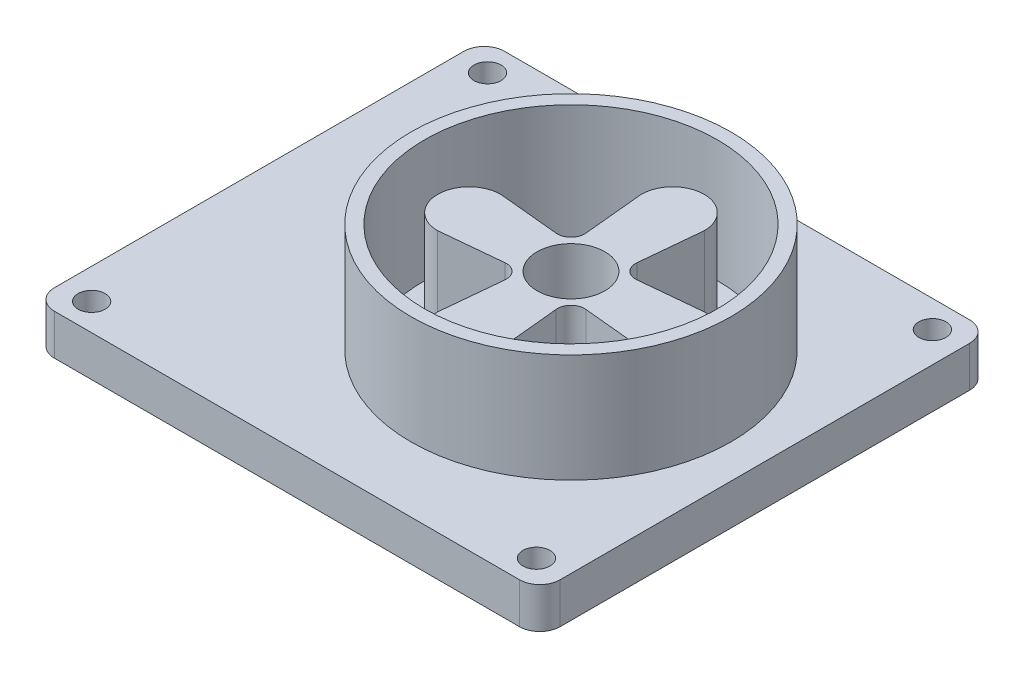
SolidWorks part; units mm, degrees
ref_plane "Front Plane" through (0, 0, 0) normal (0, 0, 1) x (1, 0, 0)
ref_plane "Top Plane" through (0, 0, 0) normal (0, 1, 0) x (1, 0, 0)
ref_plane "Right Plane" through (0, 0, 0) normal (1, 0, 0) x (0, 0, -1)
sketch "Sketch1" plane through (0, 0, 0) normal (0, 1, 0) x (1, 0, 0)
  line L0 (-11.7105, 0) -> (11.2767, 0) construction
  line L1 (-17.15, 16.6) -> (17.15, 16.6)
  line L2 (-18.65, 15.1) -> (-18.65, -15.1)
  line L3 (-17.15, -16.6) -> (17.15, -16.6)
  line L4 (18.65, 15.1) -> (18.65, -15.1)
  line L5 (-18.65, 16.6) -> (18.65, -16.6) construction
  line L6 (-18.65, -16.6) -> (18.65, 16.6) construction
  line L7 (0, 8.1415) -> (0, -7.3491) construction
  circle A0 centre (4.35, 0) radius 11.8
  arc A1 (17.15, 16.6) -> (18.65, 15.1) centre (17.15, 15.1) cw
  arc A2 (17.15, -16.6) -> (18.65, -15.1) centre (17.15, -15.1) ccw
  arc A3 (-18.65, -15.1) -> (-17.15, -16.6) centre (-17.15, -15.1) ccw
  arc A4 (-17.15, 16.6) -> (-18.65, 15.1) centre (-17.15, 15.1) ccw
  circle A5 centre (-16.403, 14.6) radius 1
  circle A6 centre (16.403, 14.6) radius 1
  circle A7 centre (16.403, -14.6) radius 1
  circle A8 centre (-16.403, -14.6) radius 1
  point P0 (0, 0)
  dimension "D3" = 23.6
  dimension "D4" = 14.3
  dimension "D5" = 1.5
  dimension "D7" = 2
  dimension "D1" = 37.3
  dimension "D2" = 33.2
  dimension "D6" = 2
extrude "Boss-Extrude1" add sketch "Sketch1" along normal blind 3
sketch "Sketch3" plane through (0, 0, 0) normal (0, 1, 0) x (1, 0, 0)
  circle A0 centre (4.35, 0) radius 11.8 construction
  circle A1 centre (4.35, 0) radius 11.8
extrude "Boss-Extrude2" add sketch "Sketch3" along normal blind 11
shell "Shell1" thickness 1
sketch "Sketch4" plane through (0, 0, 0) normal (0, -1, 0) x (1, 0, 0)
  circle A0 centre (4.35, 0) radius 2.5
  circle A1 centre (4.35, 0) radius 10.8 construction
  dimension "D1" = 5
extrude "Cut-Extrude2" cut sketch "Sketch4" against normal blind 3
sketch "Sketch5" plane through (0, 1, 0) normal (0, 1, 0) x (1, 0, 0)
  line L0 (4.35, 0) -> (4.35, 4.3525) construction
  line L1 (2.4565, 0) -> (12.9768, 0) construction
  line L2 (2.0268, 7.5057) -> (2.4652, 2.9765)
  line L3 (11.8557, 2.3232) -> (7.3265, 1.8848)
  line L4 (11.8557, -2.3232) -> (7.3265, -1.8848)
  line L5 (6.6732, 7.5057) -> (6.2348, 2.9765)
  line L6 (6.6732, -7.5057) -> (6.2348, -2.9765)
  line L7 (2.0268, -7.5057) -> (2.4652, -2.9765)
  line L8 (-3.1557, -2.3232) -> (1.3735, -1.8848)
  line L9 (-3.1557, 2.3232) -> (1.3735, 1.8848)
  arc A0 (6.6732, 7.5057) -> (2.0268, 7.5057) centre (4.35, 7.5057) ccw
  circle A2 centre (4.35, 0) radius 2.5 construction
  arc A3 (11.8557, -2.3232) -> (11.8557, 2.3232) centre (11.8557, 0) ccw
  arc A4 (2.0268, -7.5057) -> (6.6732, -7.5057) centre (4.35, -7.5057) ccw
  arc A5 (-3.1557, 2.3232) -> (-3.1557, -2.3232) centre (-3.1557, 0) ccw
  arc A6 (2.4652, -2.9765) -> (1.3735, -1.8848) centre (1.4699, -2.8801) ccw
  arc A7 (7.3265, -1.8848) -> (6.2348, -2.9765) centre (7.2301, -2.8801) ccw
  arc A8 (7.3265, 1.8848) -> (6.2348, 2.9765) centre (7.2301, 2.8801) cw
  arc A9 (2.4652, 2.9765) -> (1.3735, 1.8848) centre (1.4699, 2.8801) cw
  point P41 (4.35, 0)
  point P42 (6.1178, 1.7678)
  point P45 (2.5822, 1.7678)
  dimension "D2" = 1
  dimension "D1" = 4
extrude "Boss-Extrude4" add sketch "Sketch5" along normal blind 7
sketch "Sketch6" plane through (0, 1, 0) normal (0, -1, 0) x (1, 0, 0)
  circle A1 centre (4.35, 0) radius 2.5
  circle A2 centre (4.35, 0) radius 2.5
  dimension "D1" = 0
extrude "Cut-Extrude3" cut sketch "Sketch6" against normal through all
